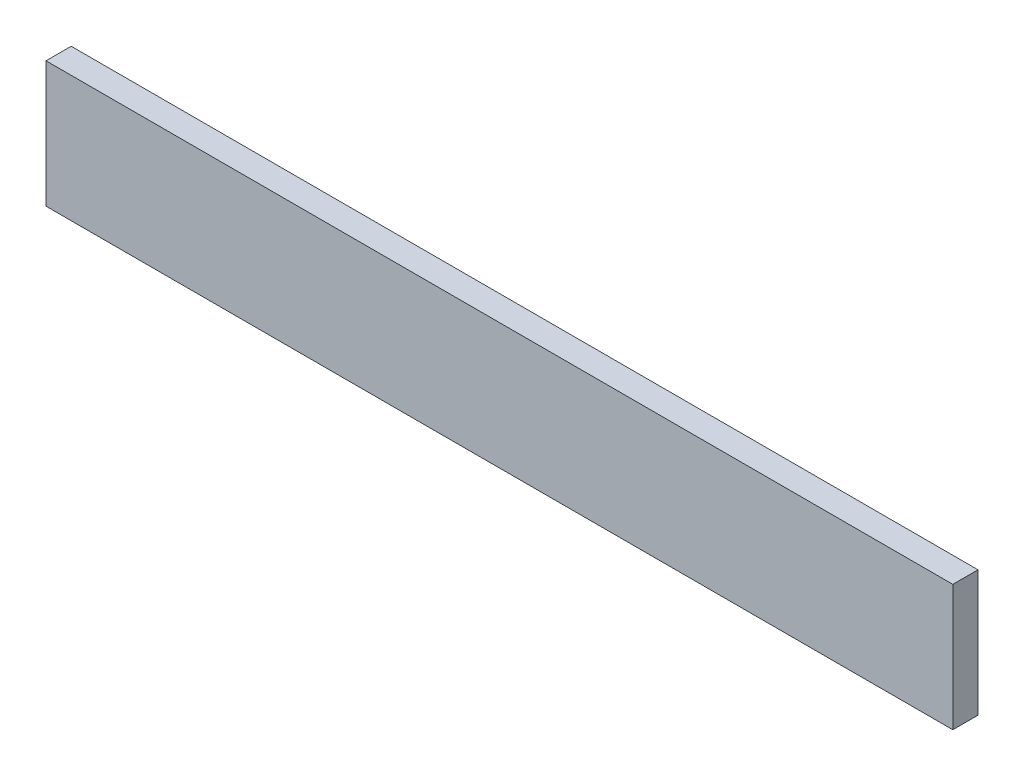
SolidWorks part; units mm, degrees
material "Pine"
ref_plane "Piano frontale" through (0, 0, 0) normal (0, 0, 1) x (1, 0, 0)
ref_plane "Piano superiore" through (0, 0, 0) normal (0, 1, 0) x (1, 0, 0)
ref_plane "Piano destro" through (0, 0, 0) normal (1, 0, 0) x (0, 0, -1)
sketch "Sketch1" plane through (0, 0, 0) normal (0, 0, 1) x (1, 0, 0)
  line L1 (0, 0) -> (54, 0)
  line L2 (0, 0) -> (0, 7.5)
  line L3 (0, 7.5) -> (54, 7.5)
  line L4 (54, 0) -> (54, 7.5)
  dimension "D1" = 54
  dimension "D2" = 7.5
extrude "Boss-Extrude1" add sketch "Sketch1" along normal blind 1.5
scale "Scale1" scale about origin uniform scaling yes scale factor 10
